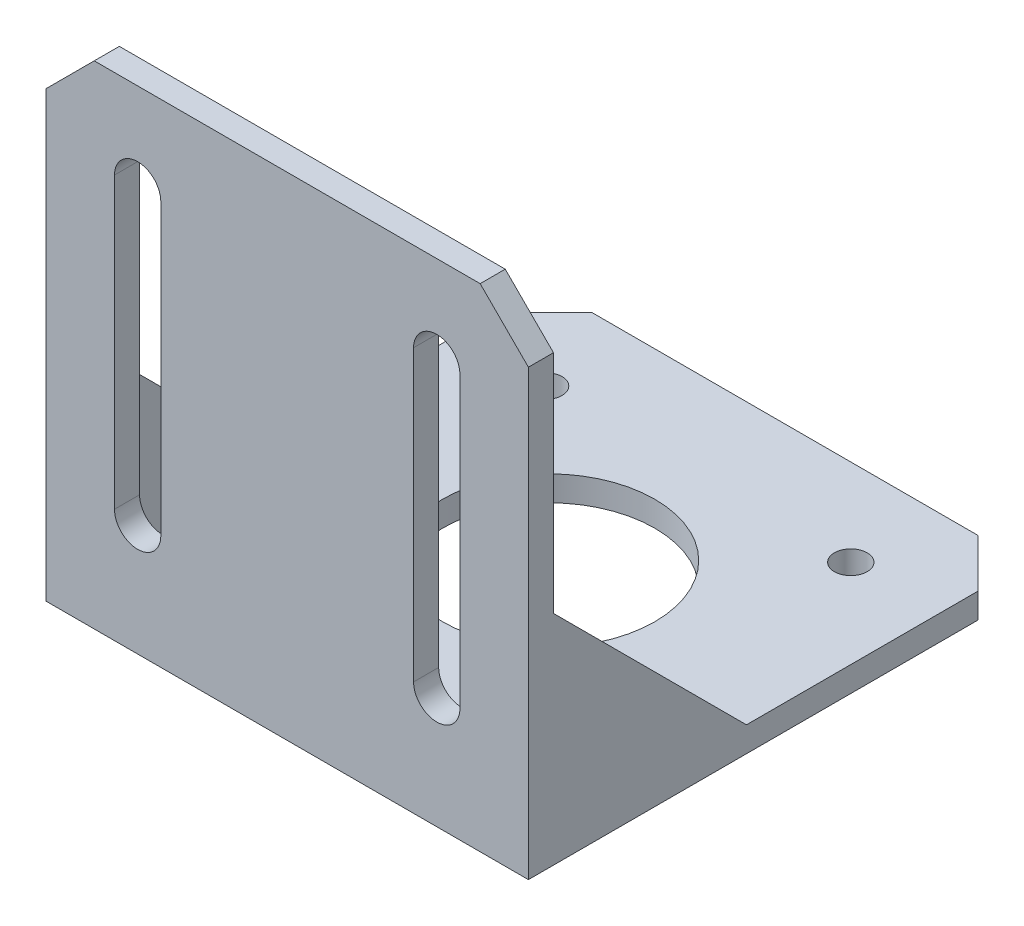
SolidWorks part; units mm, degrees
ref_plane "Front Plane" through (0, 0, 0) normal (0, 0, 1) x (1, 0, 0)
ref_plane "Top Plane" through (0, 0, 0) normal (0, 1, 0) x (1, 0, 0)
ref_plane "Right Plane" through (0, 0, 0) normal (1, 0, 0) x (0, 0, -1)
sketch "Sketch1" plane through (0, 0, 0) normal (0, 1, 0) x (1, 0, 0)
  line L1 (-25, -24.5) -> (25, -24.5)
  line L2 (-25, -24.5) -> (-25, 24.5)
  line L3 (-25, 24.5) -> (25, 24.5)
  line L4 (25, -24.5) -> (25, 24.5)
  line L5 (-25, -24.5) -> (25, 24.5) construction
  line L6 (-25, 24.5) -> (25, -24.5) construction
  line L7 (-15.8163, -15.5) -> (15.8163, -15.5) construction
  line L8 (-15.8163, -15.5) -> (-15.8163, 15.5) construction
  line L9 (-15.8163, 15.5) -> (15.8163, 15.5) construction
  line L10 (15.8163, -15.5) -> (15.8163, 15.5) construction
  line L11 (-15.8163, -15.5) -> (15.8163, 15.5) construction
  line L12 (-15.8163, 15.5) -> (15.8163, -15.5) construction
  circle A0 centre (-15.8163, 15.5) radius 1.7
  circle A1 centre (15.8163, 15.5) radius 1.7
  circle A2 centre (-15.8163, -15.5) radius 1.7
  circle A3 centre (15.8163, -15.5) radius 1.7
  circle A4 centre (0, 0) radius 11
  point P0 (0, 0)
  point P5 (0, 0)
  dimension "D3" = 31
  dimension "D4" = 3.4
  dimension "D5" = 22
  dimension "D1" = 49
  dimension "D2" = 50
extrude "Boss-Extrude1" add sketch "Sketch1" along normal blind 2.6
sketch "Sketch2" plane through (0, 0, 24.5) normal (0, 0, 1) x (1, 0, 0)
  line L0 (0, 51) -> (0, 2.6) construction
  line L1 (-25, 0) -> (25, 0)
  line L2 (-25, 0) -> (-25, 51)
  line L3 (-25, 51) -> (25, 51)
  line L4 (25, 0) -> (25, 51)
  line L5 (-15.5, 26.8) -> (0, 26.8) construction
  line L6 (15.5, 41.8) -> (15.5, 11.8) construction
  line L7 (-15.5, 41.8) -> (-15.5, 11.8) construction
  line L8 (-13.1, 41.8) -> (-13.1, 11.8)
  line L9 (-17.9, 41.8) -> (-17.9, 11.8)
  line L10 (-25, 2.6) -> (25, 2.6) construction
  line L11 (13.1, 41.8) -> (13.1, 11.8)
  line L12 (17.9, 41.8) -> (17.9, 11.8)
  line L13 (-15.5, 51) -> (-15.5, 41.8) construction
  arc A0 (-13.1, 41.8) -> (-17.9, 41.8) centre (-15.5, 41.8) ccw
  arc A1 (-17.9, 11.8) -> (-13.1, 11.8) centre (-15.5, 11.8) ccw
  arc A2 (13.1, 41.8) -> (17.9, 41.8) centre (15.5, 41.8) cw
  arc A3 (17.9, 11.8) -> (13.1, 11.8) centre (15.5, 11.8) cw
  point P14 (-15.5, 26.8)
  point P23 (15.5, 26.8)
  dimension "D4" = 2.4
  dimension "D1" = 51
  dimension "D2" = 15.5
  dimension "D3" = 30
extrude "Boss-Extrude2" add sketch "Sketch2" along normal blind 2.6
sketch "Sketch3" plane through (-25, 0, 0) normal (-1, 0, 0) x (0, 0, 1)
  line L0 (4.5, 2.6) -> (24.5, 22.6)
  line L1 (-24.5, 2.6) -> (24.5, 2.6) construction
  line L2 (24.5, 51) -> (24.5, 2.6) construction
  line L3 (24.5, 22.6) -> (24.5, 2.6)
  line L4 (24.5, 2.6) -> (4.5, 2.6)
  dimension "D1" = 20
  dimension "D2" = 20
extrude "Boss-Extrude3" add sketch "Sketch3" against normal blind 2.6
mirror "Mirror1" about plane through (0, 0, 0) normal (1, 0, 0) of "Boss-Extrude3"
chamfer "Chamfer1" distance 5 angle 45 4 edges at (25, 1.3, -24.5) (-25, 1.3, -24.5) (25, 51, 25.8) (-25, 51, 25.8)
chamfer "Chamfer2" distance 0.4 angle 45 1 edges at (0, 2.6, 24.5)
